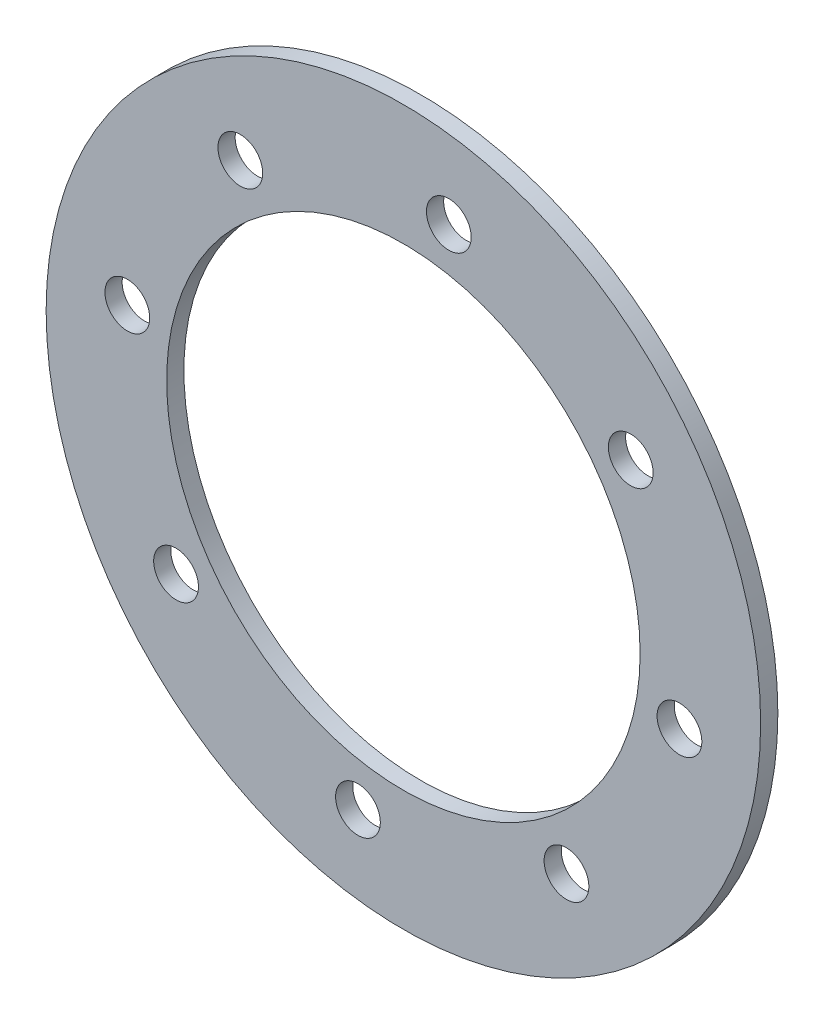
SolidWorks part; units mm, degrees
material "Thornel Mat VMA"
ref_plane "Front Plane" through (0, 0, 0) normal (0, 0, 1) x (1, 0, 0)
ref_plane "Top Plane" through (0, 0, 0) normal (0, 1, 0) x (1, 0, 0)
ref_plane "Right Plane" through (0, 0, 0) normal (1, 0, 0) x (0, 0, -1)
sketch "Sketch1" plane through (0, 0, 0) normal (0, 0, 1) x (1, 0, 0)
  circle A0 centre (0, 0) radius 27.5 construction
  circle A1 centre (0, 0) radius 27.5
  circle A2 centre (0, 0) radius 41.5
  circle A3 centre (5.2787, 32.0684) radius 2.6 construction
  circle A4 centre (26.4084, 18.9432) radius 2.6 construction
  circle A5 centre (32.0684, -5.2787) radius 2.6 construction
  circle A6 centre (18.9432, -26.4084) radius 2.6 construction
  circle A7 centre (-5.2787, -32.0684) radius 2.6 construction
  circle A8 centre (-26.4084, -18.9432) radius 2.6 construction
  circle A9 centre (-32.0684, 5.2787) radius 2.6 construction
  circle A10 centre (-18.9432, 26.4084) radius 2.6 construction
  circle A11 centre (5.2787, 32.0684) radius 2.6
  circle A12 centre (26.4084, 18.9432) radius 2.6
  circle A13 centre (32.0684, -5.2787) radius 2.6
  circle A14 centre (18.9432, -26.4084) radius 2.6
  circle A15 centre (-5.2787, -32.0684) radius 2.6
  circle A16 centre (-26.4084, -18.9432) radius 2.6
  circle A17 centre (-32.0684, 5.2787) radius 2.6
  circle A18 centre (-18.9432, 26.4084) radius 2.6
  dimension "D1" = 83
extrude "Boss-Extrude1" add sketch "Sketch1" along normal blind 2
